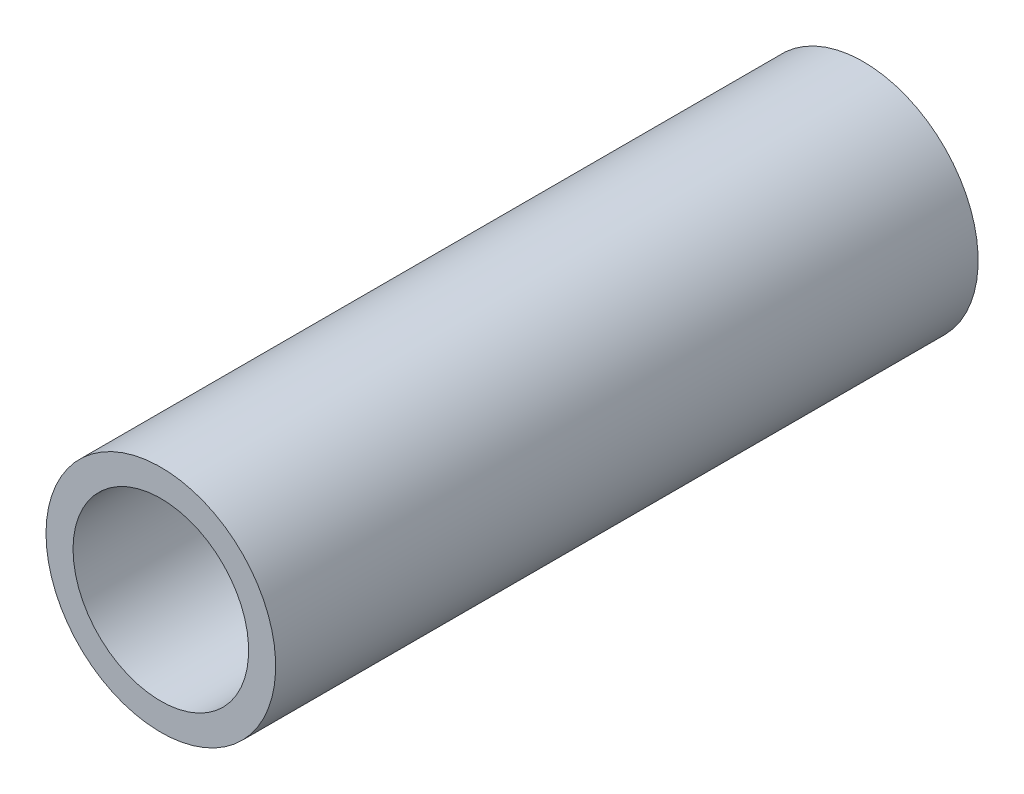
SolidWorks part; units mm, degrees
ref_plane "Piano frontale" through (0, 0, 0) normal (0, 0, 1) x (1, 0, 0)
ref_plane "Piano superiore" through (0, 0, 0) normal (0, 1, 0) x (1, 0, 0)
ref_plane "Piano destro" through (0, 0, 0) normal (1, 0, 0) x (0, 0, -1)
sketch "Schizzo1" plane through (0, 0, 0) normal (0, 0, 1) x (1, 0, 0)
  circle A0 centre (0, 0) radius 3.25
  circle A1 centre (0, 0) radius 4.25
  dimension "D1" = 6.5
  dimension "D2" = 1
extrude "Estrusione-Estrusione1" add sketch "Schizzo1" along normal blind 26
